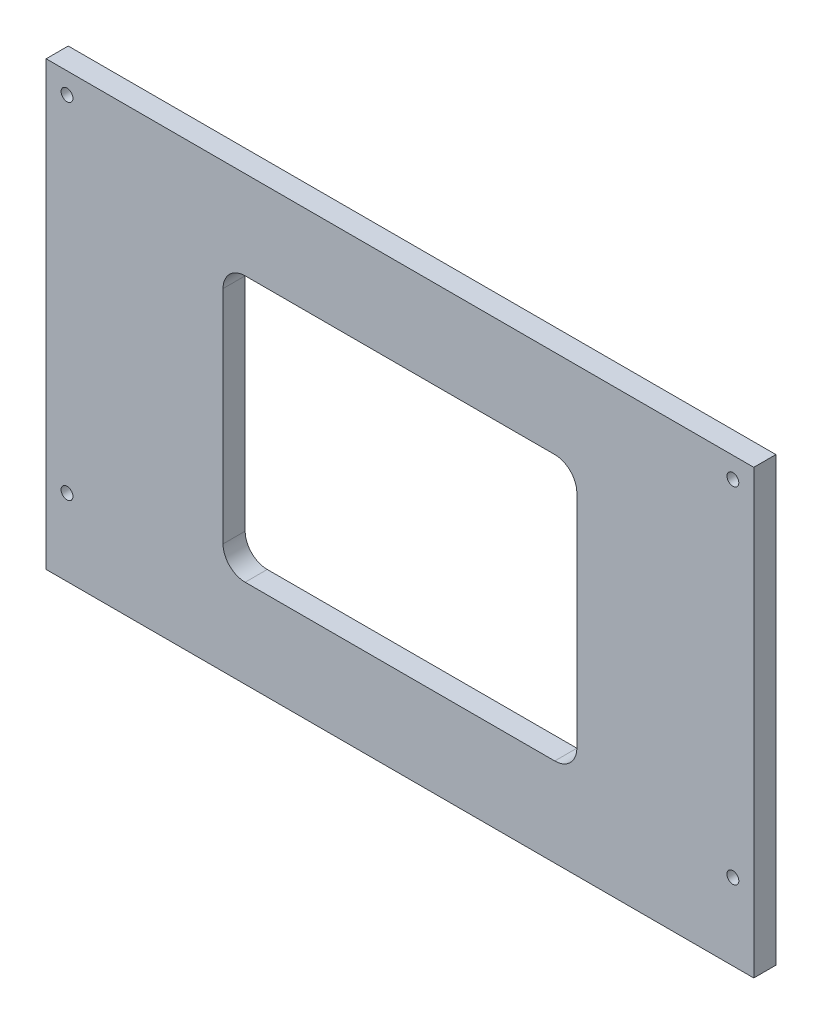
SolidWorks part; units mm, degrees
material "Acrylic (Medium-high impact)"
ref_plane "Front Plane" through (0, 0, 0) normal (0, 0, 1) x (1, 0, 0)
ref_plane "Top Plane" through (0, 0, 0) normal (0, 1, 0) x (1, 0, 0)
ref_plane "Right Plane" through (0, 0, 0) normal (1, 0, 0) x (0, 0, -1)
sketch "Sketch1" plane through (0, 0, 0) normal (0, 0, 1) x (1, 0, 0)
  line L1 (203.2, 127) -> (0, 127)
  line L2 (203.2, 127) -> (203.2, 0)
  line L3 (203.2, 0) -> (0, 0)
  line L4 (0, 127) -> (0, 0)
  line L5 (203.2, 127) -> (0, 0) construction
  line L6 (203.2, 0) -> (0, 127) construction
  point P0 (101.6, 63.5)
  dimension "D1" = 127
  dimension "D2" = 203.2
extrude "Boss-Extrude1" add sketch "Sketch1" along normal blind 6.35
hole_wizard "M3 Clearance Hole1" positions "Sketch2" profile "Sketch3" hole size "M3" standard "ANSI Metric" end condition through all
sketch "Sketch2" plane through (0, 0, 6.35) normal (0, 0, 1) x (1, 0, 0)
  line L0 (0, 127) -> (0, 0) construction
  line L1 (203.2, 127) -> (0, 127) construction
  line L2 (203.2, 0) -> (203.2, 127) construction
  line L3 (0, 0) -> (203.2, 0) construction
  point P0 (5.9944, 121.0056)
  point P2 (5.9944, 21.9964)
  point P4 (197.2056, 21.9964)
  point P6 (197.2056, 121.0056)
  dimension "D1" = 5.9944
  dimension "D2" = 5.9944
  dimension "D3" = 5.9944
  dimension "D4" = 21.9964
sketch "Sketch3" plane through (5.9944, 121.0056, 6.35) normal (1, 0, 0) x (0, -1, 0)
  line L0 (0, 0) -> (0, 6.35)
  line L1 (0, 6.35) -> (1.7, 6.35)
  line L2 (1.7, 6.35) -> (1.7, 0)
  line L5 (1.7, 0) -> (0, 0)
  line L11 (0, -6.35) -> (0, 107.95) construction
  dimension "Thru Hole Dia." = 3.4
  dimension "Thru Hole Depth" = 6.35
sketch "Sketch4" plane through (0, 0, 6.35) normal (0, 0, 1) x (1, 0, 0)
  line L0 (0, 127) -> (0, 0) construction
  line L1 (46.99, 107.95) -> (50.4952, 107.95)
  line L2 (46.99, 107.95) -> (46.99, 44.45)
  line L3 (46.99, 44.45) -> (50.4952, 44.45)
  line L4 (50.4952, 107.95) -> (50.4952, 44.45)
  line L5 (152.7048, 107.95) -> (156.21, 107.95)
  line L6 (152.7048, 107.95) -> (152.7048, 44.45)
  line L7 (152.7048, 44.45) -> (156.21, 44.45)
  line L8 (156.21, 107.95) -> (156.21, 44.45)
  line L9 (203.2, 0) -> (203.2, 127) construction
  line L10 (203.2, 127) -> (0, 127) construction
  dimension "D1" = 3.5052
  dimension "D2" = 63.5
  dimension "D3" = 46.99
  dimension "D4" = 46.99
  dimension "D5" = 19.05
extrude "Cut-Extrude1" [suppressed] cut sketch "Sketch4" against normal through all
sketch "Sketch5" plane through (0, 0, 6.35) normal (0, 0, 1) x (1, 0, 0)
  line L0 (0, 36.1092) -> (76.2, 25.4)
  line L1 (0, 127) -> (0, 0) construction
  line L2 (76.2, 25.4) -> (127, 25.4)
  line L3 (127, 25.4) -> (203.2, 36.1092)
  line L4 (203.2, 0) -> (203.2, 127) construction
  line L5 (203.2, 36.1092) -> (203.2, 0)
  line L6 (203.2, 0) -> (0, 0)
  line L7 (0, 0) -> (0, 36.1092)
  dimension "D1" = 8
  dimension "D2" = 8
  dimension "D3" = 76.2
  dimension "D4" = 76.2
  dimension "D5" = 25.4
extrude "Cut-Extrude2" [suppressed] cut sketch "Sketch5" against normal through all
sketch "Sketch6" plane through (0, 0, 6.35) normal (0, 0, 1) x (1, 0, 0)
  line L0 (0, 0) -> (203.2, 0) construction
  line L1 (50.8, 101.6) -> (152.4, 101.6)
  line L2 (50.8, 101.6) -> (50.8, 25.4)
  line L3 (50.8, 25.4) -> (152.4, 25.4)
  line L4 (152.4, 101.6) -> (152.4, 25.4)
  line L5 (50.8, 101.6) -> (152.4, 25.4) construction
  line L6 (50.8, 25.4) -> (152.4, 101.6) construction
  line L7 (0, 127) -> (0, 0) construction
  point P0 (101.6, 63.5)
  point P7 (101.6, 0)
  point P10 (0, 63.5)
  dimension "D1" = 101.6
  dimension "D2" = 76.2
extrude "Cut-Extrude3" cut sketch "Sketch6" against normal through all
fillet "Fillet1" radius 6.35 4 edges at (152.4, 101.6, 3.175) (152.4, 25.4, 3.175) (50.8, 25.4, 3.175) (50.8, 101.6, 3.175)
